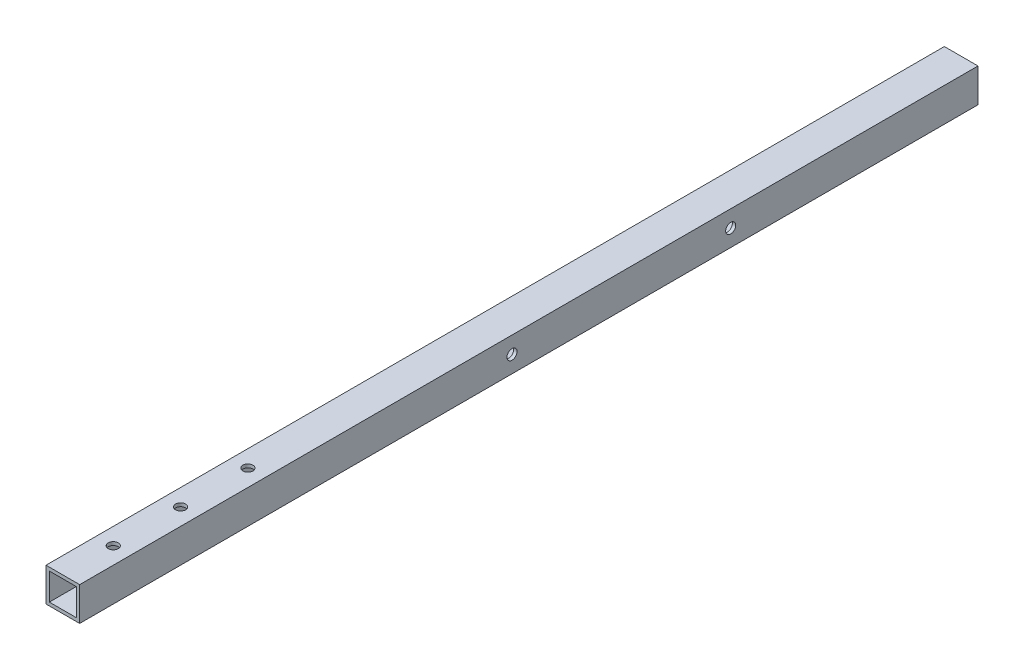
SolidWorks part; units mm, degrees
material "6063-T5"
ref_plane "前视基准面" through (0, 0, 0) normal (0, 0, 1) x (1, 0, 0)
ref_plane "上视基准面" through (0, 0, 0) normal (0, 1, 0) x (1, 0, 0)
ref_plane "右视基准面" through (0, 0, 0) normal (1, 0, 0) x (0, 0, -1)
sketch "草图1" plane through (0, 0, 0) normal (0, 0, 1) x (1, 0, 0)
  line L0 (-4, -4) -> (-4, 4)
  line L1 (-5, -5) -> (5, -5)
  line L2 (-5, -5) -> (-5, 5)
  line L3 (-5, 5) -> (5, 5)
  line L4 (5, -5) -> (5, 5)
  line L5 (0, 5) -> (0, -5) construction
  line L6 (-5, 0) -> (5, 0) construction
  line L7 (-4, 4) -> (4, 4)
  line L8 (4, -4) -> (4, 4)
  line L9 (-4, -4) -> (4, -4)
  point P0 (0, 0)
  dimension "D1" = 10
  dimension "D2" = 1
extrude "凸台-拉伸1" add sketch "草图1" along normal mid plane 267
sketch "草图2" plane through (0, -5, 0) normal (0, -1, 0) x (1, 0, 0)
  line L0 (0, 118.5) -> (0, 133.5) construction
  line L1 (-5, 133.5) -> (5, 133.5) construction
  line L2 (0, 118.5) -> (0, 98.5) construction
  line L3 (0, 98.5) -> (0, 78.5) construction
  circle A0 centre (0, 118.5) radius 1.5
  circle A1 centre (0, 98.5) radius 1.5
  circle A2 centre (0, 78.5) radius 1.5
  dimension "D1" = 3
  dimension "D2" = 15
  dimension "D3" = 20
extrude "切除-拉伸1" cut sketch "草图2" against normal mid plane 40
sketch "草图3" plane through (-5, 0, 0) normal (-1, 0, 0) x (0, 0, 1)
  line L0 (-77.5, 0) -> (22.5, 0) construction
  line L1 (-77.5, 72) -> (-77.5, -182) construction
  line L2 (22.5, 72) -> (22.5, -182) construction
  line L3 (-27.5, 0) -> (-27.5, 12.0355) construction
  circle A0 centre (-60, 0) radius 1.5
  circle A1 centre (5, 0) radius 1.5
  dimension "D1" = 3
  dimension "D2" = 65
extrude "切除-拉伸2" cut sketch "草图3" against normal blind 40
